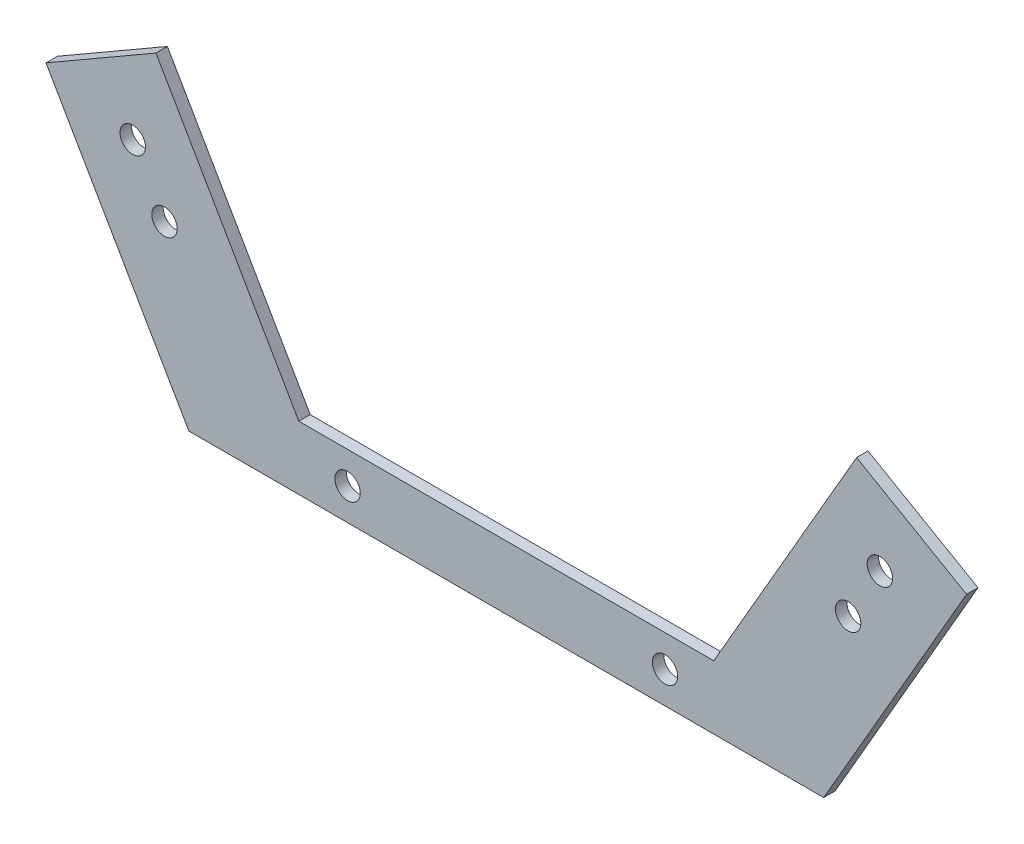
SolidWorks part; units mm, degrees
ref_plane "前基準面" through (0, 0, 0) normal (0, 0, 1) x (1, 0, 0)
ref_plane "上基準面" through (0, 0, 0) normal (0, 1, 0) x (1, 0, 0)
ref_plane "右基準面" through (0, 0, 0) normal (1, 0, 0) x (0, 0, -1)
sketch "草圖1" plane through (0, 0, 0) normal (0, 0, 1) x (1, 0, 0)
  line L8 (-40.1279, -52.3762) -> (59.8721, -52.3762)
  line L9 (59.8721, -52.3762) -> (82.3721, -13.4051)
  line L10 (82.3721, -13.4051) -> (65.0515, -3.4051)
  line L11 (65.0515, -3.4051) -> (42.5515, -42.3762)
  line L12 (42.5515, -42.3762) -> (-22.8074, -42.3762)
  line L13 (-22.8074, -42.3762) -> (-45.3074, -3.4051)
  line L14 (-45.3074, -3.4051) -> (-62.6279, -13.4051)
  line L15 (-62.6279, -13.4051) -> (-40.1279, -52.3762)
  circle A0 centre (-46.4677, -21.3954) radius 2
  circle A1 centre (66.2118, -21.3954) radius 2
  point P12 (68.7525, -21.3954)
  dimension "D14" = 4
  dimension "D1" = 100
  dimension "D2" = 120
  dimension "D3" = 270
  dimension "D4" = 120
  dimension "D5" = 240
  dimension "D6" = 90
  dimension "D7" = 270
  dimension "D8" = 120
  dimension "D9" = 20
  dimension "D10" = 20
  dimension "D11" = 45
  dimension "D12" = 45
  dimension "D13" = 10
  dimension "D15" = 10
  dimension "D16" = 15
  dimension "D17" = 10
  dimension "D18" = 15
extrude "填料-伸長2" add sketch "草圖1" along normal blind 1.8 contours L13 L14 L15 L8 L9 L10 L11 L12
sketch "草圖2" plane through (0, 0, 1.8) normal (0, 0, 1) x (1, 0, 0)
  line L0 (-22.8074, -42.3762) -> (-45.3074, -3.4051) construction
  line L1 (-45.3074, -3.4051) -> (-62.6279, -13.4051) construction
  line L2 (59.8721, -52.3762) -> (82.3721, -13.4051) construction
  line L3 (82.3721, -13.4051) -> (65.0515, -3.4051) construction
  line L4 (-62.6279, -13.4051) -> (-40.1279, -52.3762) construction
  line L5 (65.0515, -3.4051) -> (42.5515, -42.3762) construction
  line L6 (-40.1279, -52.3762) -> (59.8721, -52.3762) construction
  circle A0 centre (-48.9677, -17.0653) radius 2
  circle A1 centre (68.7118, -17.0653) radius 2
  circle A2 centre (-43.9677, -25.7256) radius 2
  circle A3 centre (63.7118, -25.7256) radius 2
  circle A4 centre (-15.1279, -47.3762) radius 2
  circle A5 centre (34.8721, -47.3762) radius 2
  point P22 (-15.0756, -48.2653)
  dimension "D1" = 10
  dimension "D2" = 10
  dimension "D3" = 10
  dimension "D4" = 10
  dimension "D5" = 20
  dimension "D6" = 10
  dimension "D7" = 10
  dimension "D8" = 20
  dimension "D9" = 25
  dimension "D10" = 5
  dimension "D11" = 25
  dimension "D12" = 5
extrude "除料-伸長3" cut sketch "草圖2" against normal blind 1.8 contours A1 | A2 | A0 | A3 | A5 | A4
